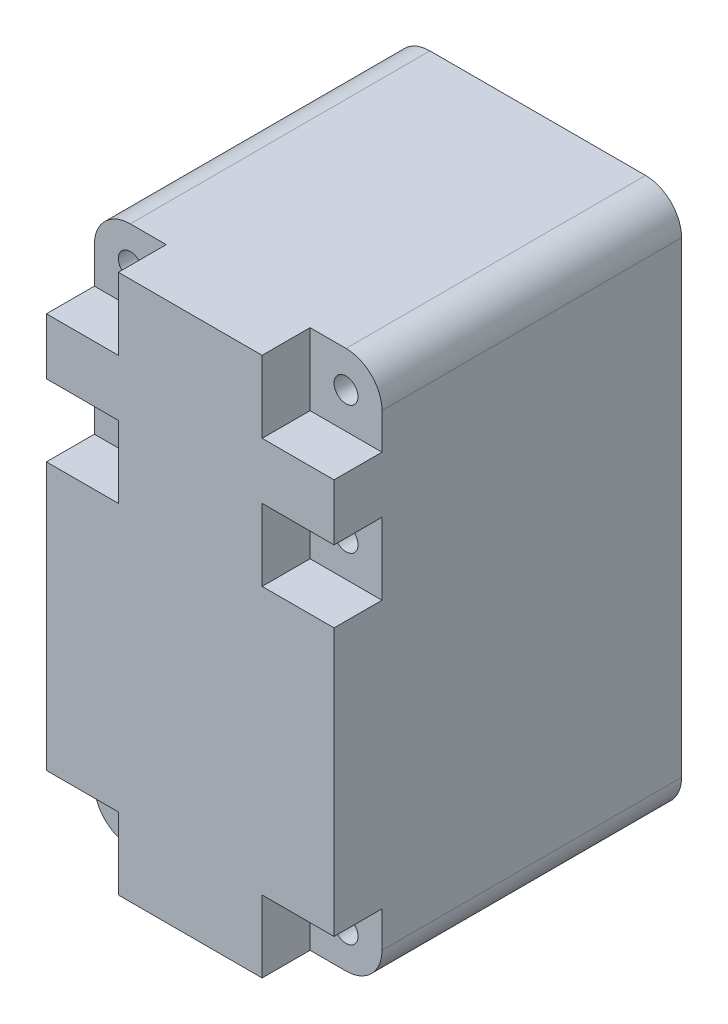
SolidWorks part; units mm, degrees
ref_plane "Plan de face" through (0, 0, 0) normal (0, 0, 1) x (1, 0, 0)
ref_plane "Plan de dessus" through (0, 0, 0) normal (0, 1, 0) x (1, 0, 0)
ref_plane "Plan de droite" through (0, 0, 0) normal (1, 0, 0) x (0, 0, -1)
sketch "Esquisse1" plane through (0, 0, 0) normal (0, 0, 1) x (1, 0, 0)
  line L1 (-9, -22.5) -> (9, -22.5)
  line L2 (-12, -19.5) -> (-12, 19.5)
  line L3 (-9, 22.5) -> (9, 22.5)
  line L4 (12, -19.5) -> (12, 19.5)
  line L5 (-12, -22.5) -> (12, 22.5) construction
  line L6 (-12, 22.5) -> (12, -22.5) construction
  arc A0 (-12, -19.5) -> (-9, -22.5) centre (-9, -19.5) ccw
  arc A1 (9, -22.5) -> (12, -19.5) centre (9, -19.5) ccw
  arc A2 (12, 19.5) -> (9, 22.5) centre (9, 19.5) ccw
  arc A3 (-12, 19.5) -> (-9, 22.5) centre (-9, 19.5) cw
  point P0 (0, 0)
  dimension "D3" = 3
  dimension "D1" = 24
  dimension "D2" = 45
extrude "Boss.-Extru.1" add sketch "Esquisse1" along normal mid plane 29
sketch "Esquisse2" plane through (0, 0, 14.5) normal (0, 0, 1) x (1, 0, 0)
  line L1 (-9, -19.5) -> (9, -19.5) construction
  line L2 (-9, -19.5) -> (-9, 19.5) construction
  line L3 (-9, 19.5) -> (9, 19.5) construction
  line L4 (9, -19.5) -> (9, 19.5) construction
  line L5 (-9, -19.5) -> (9, 19.5) construction
  line L6 (-9, 19.5) -> (9, -19.5) construction
  circle A0 centre (9, 19.5) radius 1
  circle A1 centre (-9, 19.5) radius 1
  circle A2 centre (-9, 8.8) radius 1
  circle A3 centre (9, 8.8) radius 1
  circle A4 centre (-9, -19.5) radius 1
  circle A5 centre (9, -19.5) radius 1
  point P0 (0, 0)
extrude "Enlèv. mat.-Extru.1" cut sketch "Esquisse2" against normal blind 9
sketch "Esquisse4" plane through (0, 0, 14.5) normal (0, 0, 1) x (1, 0, 0)
  line L0 (-9, 8.8) -> (9, 8.8) construction
  line L1 (-9, 19.5) -> (9, 19.5) construction
  line L2 (-9, 19.5) -> (-9, -19.5) construction
  line L3 (-9, -19.5) -> (9, -19.5) construction
  line L4 (9, 19.5) -> (9, -19.5) construction
  line L6 (9, 22.5) -> (-9, 22.5) construction
  line L7 (-12, 16.5) -> (-6, 16.5)
  line L8 (-12, 16.5) -> (-12, 22.5)
  line L9 (-12, 22.5) -> (-6, 22.5)
  line L10 (-6, 16.5) -> (-6, 22.5)
  line L11 (-12, 16.5) -> (-6, 22.5) construction
  line L12 (12, -19.5) -> (12, 19.5) construction
  line L14 (12, 16.5) -> (6, 16.5)
  line L15 (12, 16.5) -> (12, 22.5)
  line L16 (12, 22.5) -> (6, 22.5)
  line L17 (6, 16.5) -> (6, 22.5)
  line L18 (12, 16.5) -> (6, 22.5) construction
  line L19 (6, 5.8) -> (12, 5.8)
  line L20 (6, 5.8) -> (6, 11.8)
  line L21 (6, 11.8) -> (12, 11.8)
  line L22 (12, 5.8) -> (12, 11.8)
  line L23 (6, 5.8) -> (12, 11.8) construction
  line L24 (6, 11.8) -> (12, 5.8) construction
  line L25 (-12, 19.5) -> (-12, -19.5) construction
  line L26 (-6, 5.8) -> (-12, 5.8)
  line L27 (-6, 5.8) -> (-6, 11.8)
  line L28 (-6, 11.8) -> (-12, 11.8)
  line L29 (-12, 5.8) -> (-12, 11.8)
  line L30 (-6, 5.8) -> (-12, 11.8) construction
  line L31 (-6, 11.8) -> (-12, 5.8) construction
  line L32 (-9, -22.5) -> (9, -22.5) construction
  line L33 (-12, -16.5) -> (-6, -16.5)
  line L34 (-12, -16.5) -> (-12, -22.5)
  line L35 (-12, -22.5) -> (-6, -22.5)
  line L36 (-6, -16.5) -> (-6, -22.5)
  line L37 (-12, -16.5) -> (-6, -22.5) construction
  line L38 (-12, -22.5) -> (-6, -16.5) construction
  line L39 (-12, 22.5) -> (-6, 16.5) construction
  line L40 (12, -16.5) -> (6, -16.5)
  line L41 (12, -16.5) -> (12, -22.5)
  line L42 (12, -22.5) -> (6, -22.5)
  line L43 (6, -16.5) -> (6, -22.5)
  line L44 (12, -16.5) -> (6, -22.5) construction
  line L45 (12, -22.5) -> (6, -16.5) construction
  line L46 (12, 22.5) -> (6, 16.5) construction
  dimension "D1" = 6
extrude "Enlèv. mat.-Extru.2" cut sketch "Esquisse4" against normal blind 4
